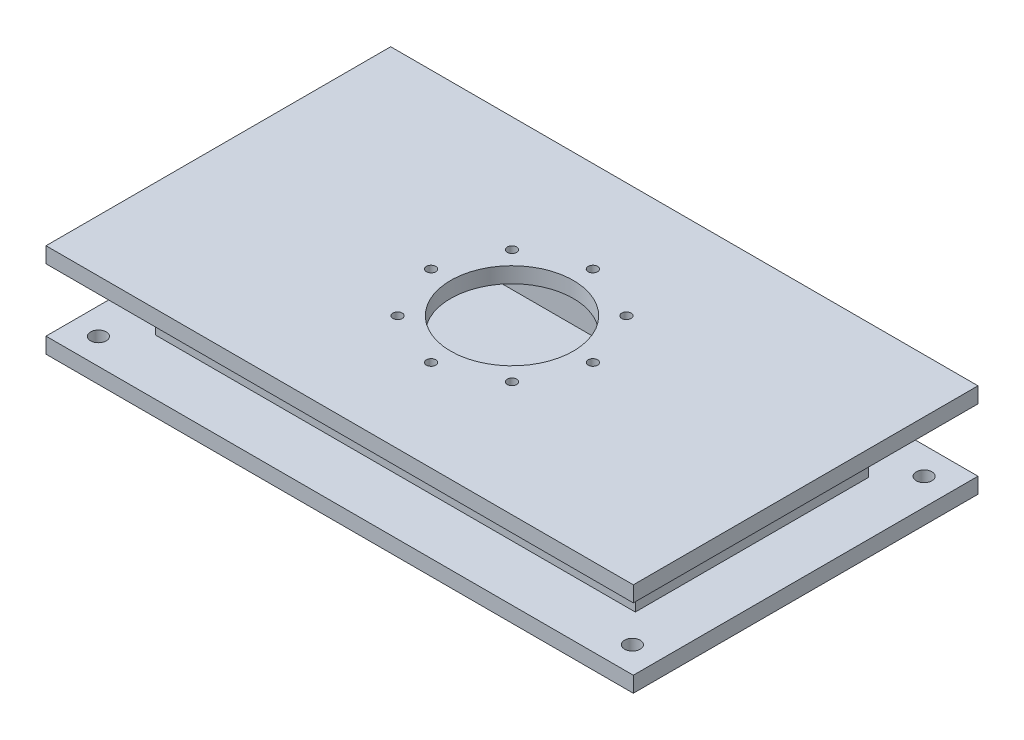
SolidWorks part; units mm, degrees
ref_plane "Front Plane" through (0, 0, 0) normal (0, 0, 1) x (1, 0, 0)
ref_plane "Top Plane" through (0, 0, 0) normal (0, 1, 0) x (1, 0, 0)
ref_plane "Right Plane" through (0, 0, 0) normal (1, 0, 0) x (0, 0, -1)
sketch "Sketch1" plane through (0, 0, 0) normal (0, 1, 0) x (1, 0, 0)
  line L1 (-51.269, 25.9043) -> (61.253, 25.9043)
  line L2 (-51.269, 25.9043) -> (-51.269, -40.1357)
  line L3 (-51.269, -40.1357) -> (61.253, -40.1357)
  line L4 (61.253, 25.9043) -> (61.253, -40.1357)
  circle A0 centre (-46.2077, 20.7265) radius 1.5
  circle A1 centre (56.1004, 20.7265) radius 1.5
  circle A2 centre (56.1004, -35.1559) radius 1.5
  circle A3 centre (-46.2077, -35.1559) radius 1.5
  dimension "D3" = 3
  dimension "D4" = 3
  dimension "D5" = 3
  dimension "D6" = 3
  dimension "D1" = 112.522
  dimension "D2" = 66.04
extrude "Boss-Extrude1" add sketch "Sketch1" along normal blind 3
sketch "Sketch4" plane through (0, 3, 0) normal (0, 1, 0) x (1, 0, 0)
  line L1 (-40.982, 15.2363) -> (50.966, 15.2363)
  line L2 (-40.982, 15.2363) -> (-40.982, -29.4677)
  line L3 (-40.982, -29.4677) -> (50.966, -29.4677)
  line L4 (50.966, 15.2363) -> (50.966, -29.4677)
  line L5 (-51.269, 25.9043) -> (-51.269, -40.1357) construction
  line L6 (61.253, -40.1357) -> (61.253, 25.9043) construction
  line L7 (61.253, 25.9043) -> (-51.269, 25.9043) construction
  line L8 (-51.269, -40.1357) -> (61.253, -40.1357) construction
  dimension "D1" = 10.287
  dimension "D2" = 10.287
  dimension "D3" = 10.668
  dimension "D4" = 10.668
extrude "Boss-Extrude2" add sketch "Sketch4" along normal blind 12 contours L1 L4 L3 L2
shell "Shell1" thickness 2.54
sketch "Sketch13" plane through (0, 0, 29.4677) normal (0, 0, 1) x (1, 0, 0)
  circle A0 centre (-28.8928, 9.1185) radius 3.2534
extrude "Cut-Extrude1" cut sketch "Sketch13" against normal blind 8.19
sketch "Sketch15" plane through (-40.982, 0, 0) normal (-1, 0, 0) x (0, 0, 1)
  circle A0 centre (-6.6934, 8.1974) radius 3.3938
extrude "Cut-Extrude2" cut sketch "Sketch15" against normal blind 8.19
sketch "Sketch16" plane through (0, 15, 0) normal (0, 1, 0) x (1, 0, 0)
  line L1 (-51.269, 25.9043) -> (61.253, 25.9043)
  line L2 (-51.269, 25.9043) -> (-51.269, -40.1357)
  line L3 (-51.269, -40.1357) -> (61.253, -40.1357)
  line L4 (61.253, 25.9043) -> (61.253, -40.1357)
  circle A0 centre (4.992, -7.1157) radius 11.75
  circle A2 centre (4.992, 8.3843) radius 0.9029
  circle A3 centre (-5.9682, 3.8445) radius 0.9029
  circle A4 centre (-10.508, -7.1157) radius 0.9029
  circle A5 centre (-5.9682, -18.0758) radius 0.9029
  circle A6 centre (4.992, -22.6157) radius 0.9029
  circle A7 centre (15.9521, -18.0758) radius 0.9029
  circle A8 centre (20.492, -7.1157) radius 0.9029
  circle A9 centre (15.9521, 3.8445) radius 0.9029
  dimension "D1" = 23.5
  dimension "D2" = 15.5
  dimension "D3" = 1.8058
  dimension "D4" = 8
extrude "Boss-Extrude4" add sketch "Sketch16" along normal blind 3
